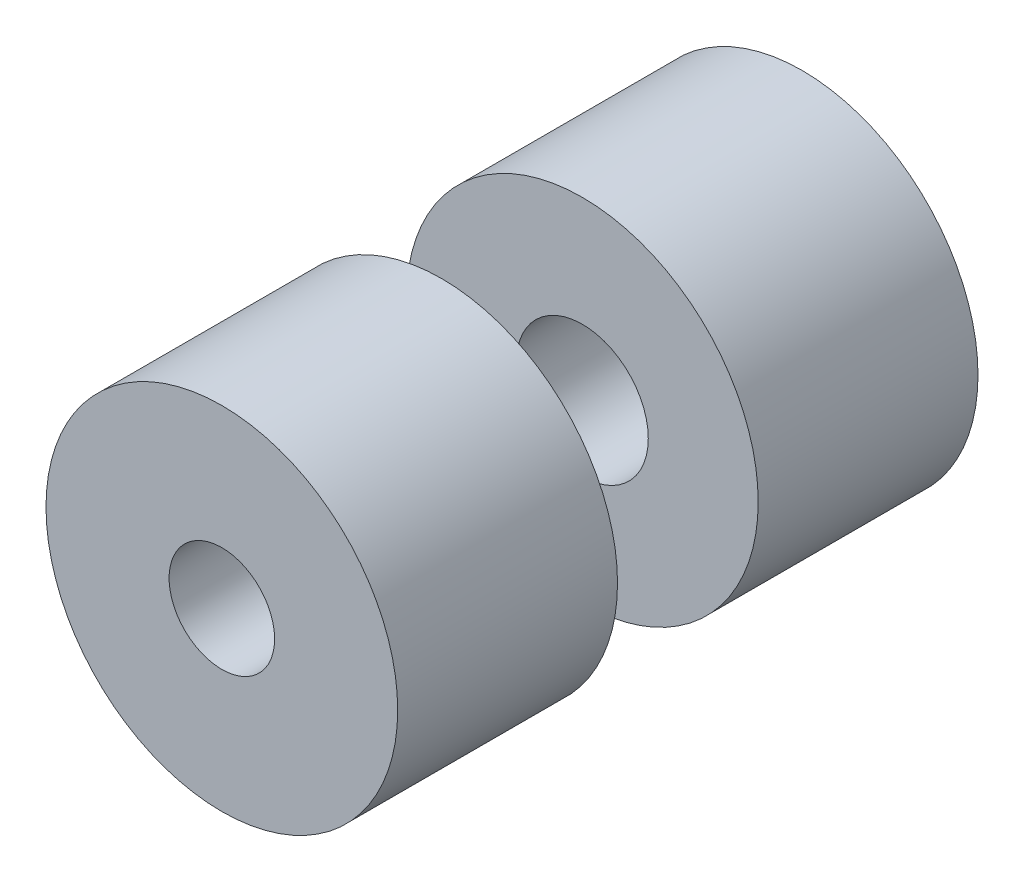
SolidWorks part; units mm, degrees
ref_plane "前视基准面" through (0, 0, 0) normal (0, 0, 1) x (1, 0, 0)
ref_plane "上视基准面" through (0, 0, 0) normal (0, 1, 0) x (1, 0, 0)
ref_plane "右视基准面" through (0, 0, 0) normal (1, 0, 0) x (0, 0, -1)
other "Configuration Table"
sketch "草图1" plane through (0, 0, 0) normal (1, 0, 0) x (0, 0, -1)
  line L0 (9, 0) -> (85, 0) construction
  line L1 (14, 6) -> (14, 20)
  line L2 (14, 20) -> (39, 20)
  line L3 (39, 20) -> (39, 6)
  line L4 (39, 6) -> (14, 6)
  line L5 (55, 7.5) -> (55, 20)
  line L6 (55, 20) -> (80, 20)
  line L7 (80, 20) -> (80, 7.5)
  line L8 (80, 7.5) -> (55, 7.5)
revolve "旋转1" add sketch "草图1" angle 360 about L0
